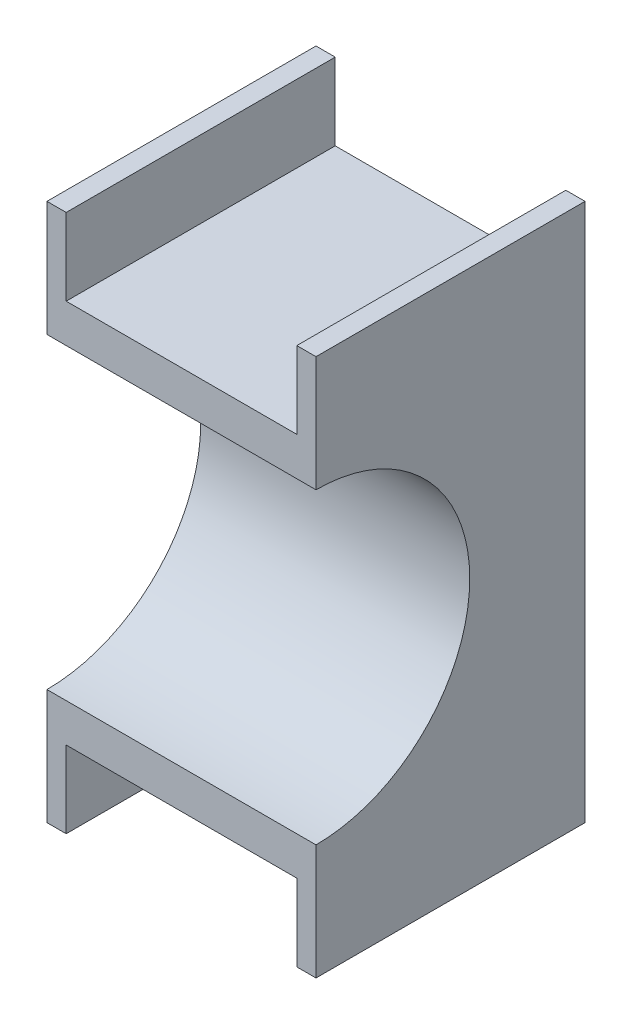
SolidWorks part; units mm, degrees
ref_plane "Plan de face" through (0, 0, 0) normal (0, 0, 1) x (1, 0, 0)
ref_plane "Plan de dessus" through (0, 0, 0) normal (0, 1, 0) x (1, 0, 0)
ref_plane "Plan de droite" through (0, 0, 0) normal (1, 0, 0) x (0, 0, -1)
sketch "Esquisse1" plane through (0, 0, 0) normal (0, 0, 1) x (1, 0, 0)
  line L1 (-1.5, 3.5) -> (2, 3.5)
  line L2 (-1.5, 3.5) -> (-1.5, -3.5)
  line L3 (-1.5, -3.5) -> (2, -3.5)
  line L4 (2, 3.5) -> (2, -3.5)
  dimension "D1" = 1.5
  dimension "D2" = 2
  dimension "D3" = 3.5
  dimension "D4" = 3.5
extrude "Boss.-Extru.1" add sketch "Esquisse1" along normal blind 3.5
sketch "Esquisse2" plane through (0, 3.5, 0) normal (0, 1, 0) x (1, 0, 0)
  line L0 (2, 0) -> (-1.5, 0) construction
  line L1 (-1.25, 0) -> (1.75, 0)
  line L2 (-1.25, 0) -> (-1.25, -3.5)
  line L3 (-1.25, -3.5) -> (1.75, -3.5)
  line L4 (1.75, 0) -> (1.75, -3.5)
  line L5 (2, -3.5) -> (-1.5, -3.5) construction
  line L6 (-1.5, -3.5) -> (-1.5, 0) construction
  dimension "D1" = 3
  dimension "D2" = 0.25
extrude "Enlèv. mat.-Extru.1" cut sketch "Esquisse2" against normal blind 1 contours L2 L1 L4 L3
sketch "Esquisse3" plane through (0, -3.5, 0) normal (0, -1, 0) x (-1, 0, 0)
  line L0 (1.5, 0) -> (-2, 0) construction
  line L1 (-1.75, 0) -> (1.25, 0)
  line L2 (-1.75, 0) -> (-1.75, -3.5)
  line L3 (-1.75, -3.5) -> (1.25, -3.5)
  line L4 (1.25, 0) -> (1.25, -3.5)
  line L5 (1.5, -3.5) -> (-2, -3.5) construction
  line L6 (-2, -3.5) -> (-2, 0) construction
  dimension "D1" = 0.25
  dimension "D2" = 3
extrude "Enlèv. mat.-Extru.2" cut sketch "Esquisse3" against normal blind 1 contours L2 L1 L4 L3
sketch "Esquisse5" plane through (2, 0, 0) normal (1, 0, 0) x (0, 0, -1)
  line L0 (-3.5, -3.5) -> (-3.5, 3.5) construction
  line L1 (-3.5, -2) -> (-3.5, 2)
  arc A0 (-3.5, -2) -> (-3.5, 2) centre (-3.5, 0) ccw
  dimension "D1" = 2
extrude "Enlèv. mat.-Extru.4" cut sketch "Esquisse5" against normal blind 10 contours L1 A0
